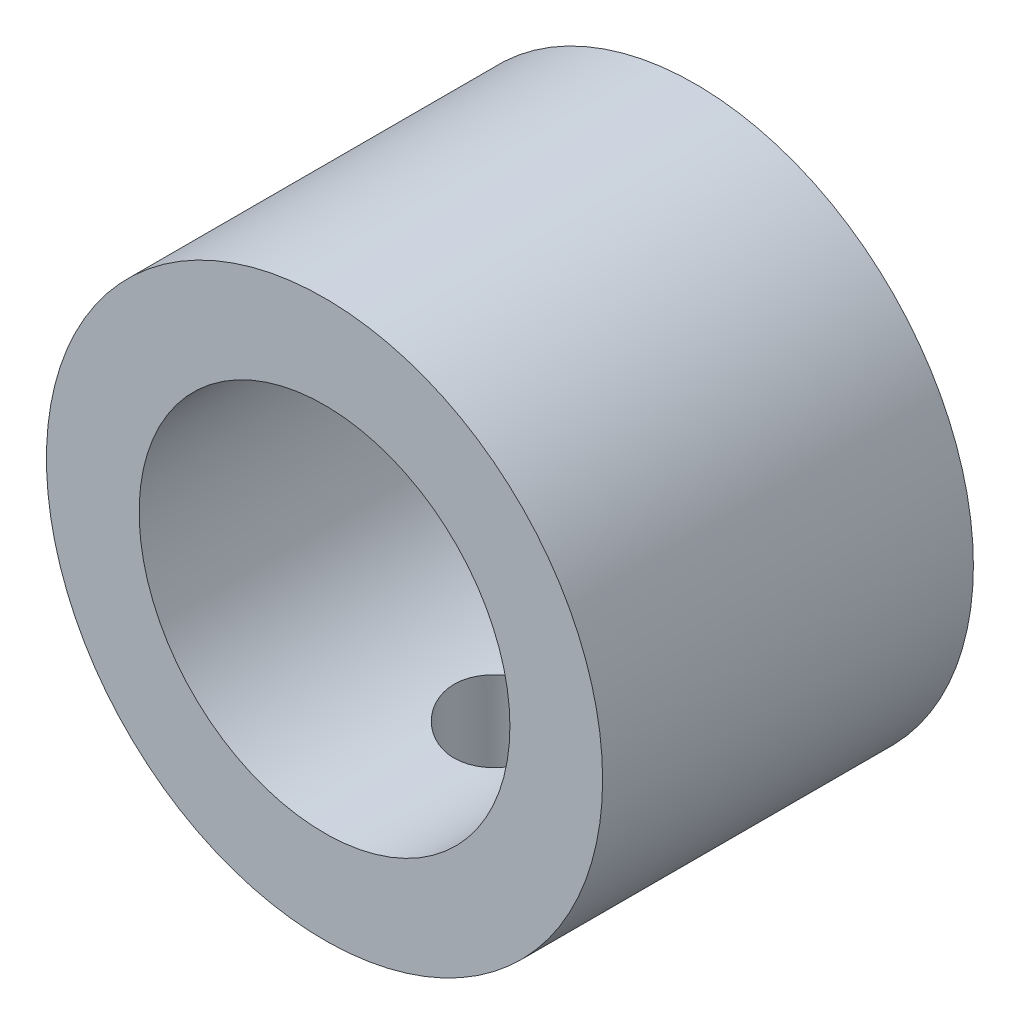
SolidWorks part; units mm, degrees
ref_plane "Front Plane" through (0, 0, 0) normal (0, 0, 1) x (1, 0, 0)
ref_plane "Top Plane" through (0, 0, 0) normal (0, 1, 0) x (1, 0, 0)
ref_plane "Right Plane" through (0, 0, 0) normal (1, 0, 0) x (0, 0, -1)
sketch "Sketch1" plane through (0, 0, 0) normal (0, 0, 1) x (1, 0, 0)
  circle A0 centre (0, 0) radius 7.5
  circle A1 centre (0, 0) radius 5
  dimension "D1" = 10
  dimension "D2" = 15
extrude "Boss-Extrude1" add sketch "Sketch1" along normal mid plane 10
sketch "Sketch2" plane through (0, 0, 0) normal (0, 1, 0) x (1, 0, 0)
  circle A0 centre (0, 0) radius 1.5
  dimension "D1" = 3
extrude "Cut-Extrude1" cut sketch "Sketch2" against normal up to surface (7.5 mm away)
